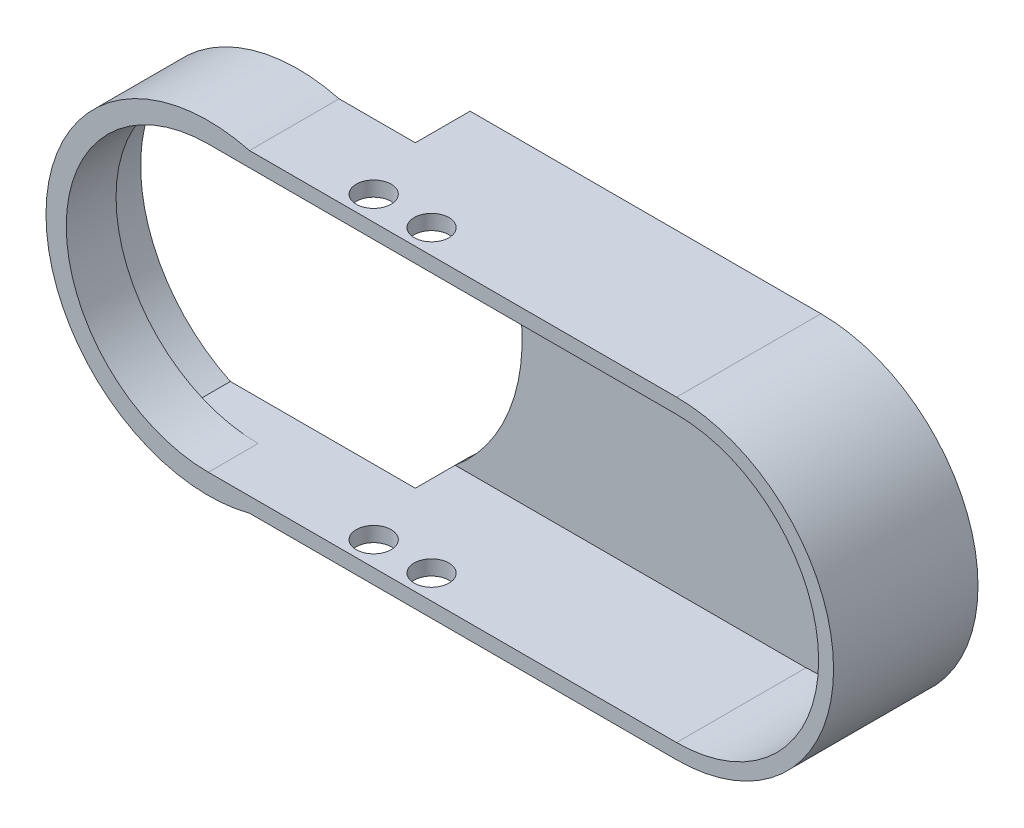
SolidWorks part; units mm, degrees
ref_plane "Front Plane" through (0, 0, 0) normal (0, 0, 1) x (1, 0, 0)
ref_plane "Top Plane" through (0, 0, 0) normal (0, 1, 0) x (1, 0, 0)
ref_plane "Right Plane" through (0, 0, 0) normal (1, 0, 0) x (0, 0, -1)
sketch "Sketch5" plane through (0, 0, 0) normal (0, 0, 1) x (1, 0, 0)
  line L5 (-35.2234, 28.535) -> (-35.2234, 31.535)
  line L6 (-35.2234, 31.535) -> (35.2234, 31.535)
  line L9 (-35.2234, -28.535) -> (-35.2234, -31.535)
  line L10 (-35.2234, -31.535) -> (35.2234, -31.535)
  arc A2 (-35.2234, 28.535) -> (-35.2234, -28.535) centre (-58.7766, 0) cw
  arc A3 (35.2234, -31.535) -> (35.2234, 31.535) centre (35.2234, 0) ccw
  point P1 (0, 0)
  point P6 (18.1699, 0)
  point P7 (0, 31.535)
  point P8 (-35.2234, 28.535)
  dimension "D2" = 37
  dimension "D3" = 31.535
  dimension "D5" = 31.535
  dimension "D1" = 94
  dimension "D4" = 3
extrude "Boss-Extrude2" add sketch "Sketch5" along normal blind 3 separate body
sketch "Sketch7" plane through (0, 0, 3) normal (0, 0, 1) x (1, 0, 0)
  line L0 (35.2234, 31.535) -> (-35.2234, 31.535)
  line L1 (-35.2234, 31.535) -> (-35.2234, 28.535)
  line L2 (35.2234, -31.535) -> (-35.2234, -31.535)
  line L3 (-35.2234, -31.535) -> (-35.2234, -28.535)
  line L4 (-35.2234, 28.535) -> (35.2234, 28.535)
  line L5 (-35.2234, -28.535) -> (35.2234, -28.535)
  line L6 (35.2234, 31.535) -> (-35.2234, 31.535) construction
  arc A0 (35.2234, -31.535) -> (35.2234, 31.535) centre (35.2234, 0) ccw
  arc A1 (35.2234, -28.535) -> (35.2234, 28.535) centre (35.2234, 0) ccw
  point P0 (-35.2234, -31.535)
  point P3 (0, 0)
  point P8 (0, 0)
  point P9 (0, 0)
  dimension "D1" = 31.535
  dimension "D2" = 28.535
  dimension "D3" = 3
extrude "Boss-Extrude3" add sketch "Sketch7" along normal blind 26
sketch "Sketch8" plane through (0, 31.535, 0) normal (0, 1, 0) x (1, 0, 0)
  line L0 (35.2234, -29) -> (-35.2234, -29) construction
  line L1 (-35.2234, -29) -> (-35.2234, 0) construction
  circle A0 centre (-18.8434, -24.12) radius 3.5
  circle A1 centre (-30.4634, -24.12) radius 3.5
  point P4 (0, 0)
  point P7 (0, 0)
  point P9 (-30.7041, -21.2139)
  point P11 (-24.254, -23.87)
  dimension "D1" = 7
  dimension "D2" = 4.88
  dimension "D3" = 4.76
  dimension "D4" = 11.62
extrude "Cut-Extrude1" cut sketch "Sketch8" against normal through all
sketch "Sketch9" plane through (0, 0, 29) normal (0, 0, 1) x (1, 0, 0)
  line L1 (-50.5154, 31.535) -> (-35.2234, 31.535)
  line L3 (-50.5154, -31.535) -> (-35.2234, -31.535)
  line L4 (-35.2234, -28.535) -> (-35.2234, -31.535)
  line L5 (-35.2234, 31.535) -> (-35.2234, 28.535)
  line L6 (-58.78, 28.535) -> (-35.2234, 28.535)
  line L7 (-35.2234, -28.535) -> (-58.78, -28.535)
  arc A0 (-50.5154, -31.535) -> (-50.5154, 31.535) centre (-58.78, 0) cw
  arc A1 (-58.78, -28.535) -> (-58.78, 28.535) centre (-58.78, 0) cw
  dimension "D1" = 28.535
  dimension "D2" = 32.6
  dimension "D3" = 58.78
extrude "Boss-Extrude4" add sketch "Sketch9" against normal blind 10
sketch "Sketch11" plane through (0, 0, 19) normal (0, 0, -1) x (-1, 0, 0)
  line L0 (72.3562, 28.535) -> (35.2234, 28.535)
  line L1 (50.5154, 31.535) -> (35.2234, 31.535)
  line L4 (35.2234, -31.535) -> (35.2234, -28.535)
  line L5 (35.2234, 31.535) -> (35.2234, 28.535)
  line L6 (50.5154, -31.535) -> (35.2234, -31.535) construction
  line L7 (35.2234, -31.535) -> (-35.2234, -31.535) construction
  line L8 (72.3562, -28.535) -> (35.2234, -28.535)
  line L9 (50.5154, -31.535) -> (35.2234, -31.535)
  arc A2 (72.3562, -28.535) -> (72.3562, 28.535) centre (58.78, 0) ccw
  arc A3 (50.5154, -31.535) -> (50.5154, 31.535) centre (58.78, 0) ccw
  point P1 (50.5154, -31.535)
  point P2 (67.0446, 31.535)
  point P4 (50.5154, 31.535)
  dimension "D1" = 32.6
  dimension "D2" = 31.6
extrude "Boss-Extrude5" add sketch "Sketch11" along normal blind 8
